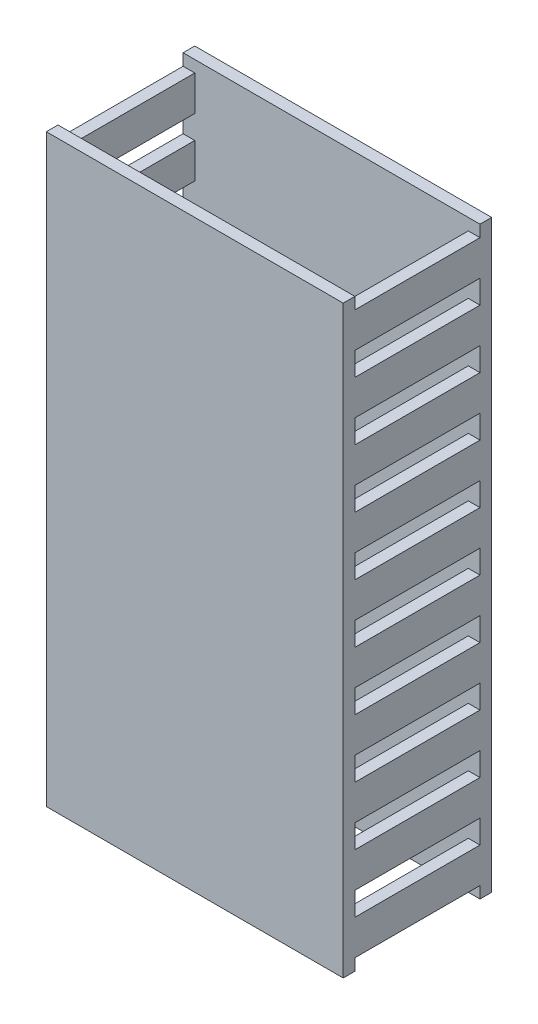
SolidWorks part; units mm, degrees
ref_plane "Front Plane" through (0, 0, 0) normal (0, 0, 1) x (1, 0, 0)
ref_plane "Top Plane" through (0, 0, 0) normal (0, 1, 0) x (1, 0, 0)
ref_plane "Right Plane" through (0, 0, 0) normal (1, 0, 0) x (0, 0, -1)
sketch "Sketch1" plane through (0, 0, 0) normal (0, 1, 0) x (1, 0, 0)
  line L0 (0, 25.4) -> (50.8, 0) construction
  line L1 (0, 0) -> (50.8, 0)
  line L2 (0, 0) -> (0, 25.4)
  line L3 (0, 25.4) -> (50.8, 25.4)
  line L4 (50.8, 0) -> (50.8, 25.4)
  line L6 (2, 23.4) -> (48.8, 23.4)
  line L7 (2, 23.4) -> (2, 2)
  line L8 (2, 2) -> (48.8, 2)
  line L9 (48.8, 23.4) -> (48.8, 2)
  line L10 (2, 23.4) -> (48.8, 2) construction
  line L11 (2, 2) -> (48.8, 23.4) construction
  point P5 (25.4, 12.7)
  dimension "D1" = 50.8
  dimension "D2" = 25.4
  dimension "D3" = 2
  dimension "D4" = 2
extrude "Boss-Extrude1" add sketch "Sketch1" along normal mid plane 100
sketch "Sketch2" plane through (50.8, 0, 0) normal (1, 0, 0) x (0, 0, -1)
  line L0 (2, 50) -> (2, -50) construction
  line L1 (2, 50) -> (2, -50)
  line L2 (23.4, 50) -> (23.4, -50) construction
  line L3 (23.4, 50) -> (23.4, -50)
  line L4 (23.4, 0) -> (2, 0) construction
  line L6 (2, 2) -> (23.4, 2)
  line L7 (2, 2) -> (2, -2)
  line L8 (2, -2) -> (23.4, -2)
  line L9 (23.4, 2) -> (23.4, -2)
  line L10 (2, 2) -> (23.4, -2) construction
  line L11 (2, -2) -> (23.4, 2) construction
  point P6 (12.7, 0)
  dimension "D1" = 4
extrude "Cut-Extrude1" cut sketch "Sketch2" against normal through all contours L1 L8 L3 L6
pattern_linear "LPattern1" count 6 spacing 10 along (0, -1, 0) count 6 spacing 10 along (0, 1, 0) of "Cut-Extrude1"
